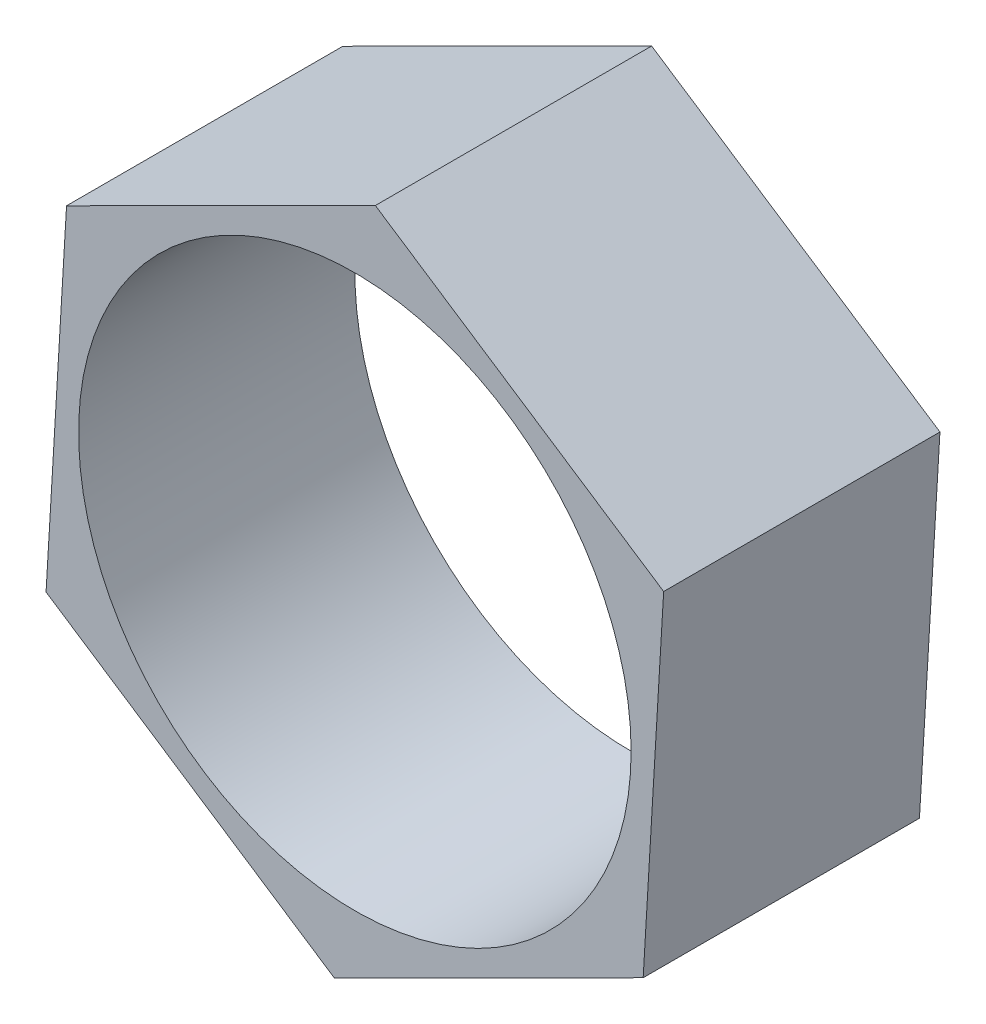
SolidWorks part; units mm, degrees
ref_plane "Front Plane" through (0, 0, 0) normal (0, 0, 1) x (1, 0, 0)
ref_plane "Top Plane" through (0, 0, 0) normal (0, 1, 0) x (1, 0, 0)
ref_plane "Right Plane" through (0, 0, 0) normal (1, 0, 0) x (0, 0, -1)
sketch "Sketch1" plane through (0, 0, 0) normal (0, 0, 1) x (1, 0, 0)
  line L1 (0.0742, 1.2478) -> (-1.0435, 0.6881)
  line L2 (-1.0435, 0.6881) -> (-1.1177, -0.5597)
  line L3 (-1.1177, -0.5597) -> (-0.0742, -1.2478)
  line L4 (-0.0742, -1.2478) -> (1.0435, -0.6881)
  line L5 (1.0435, -0.6881) -> (1.1177, 0.5597)
  line L6 (1.1177, 0.5597) -> (0.0742, 1.2478)
  circle A0 centre (0, 0) radius 1
  circle A1 centre (0, 0) radius 1.0825 construction
  point P3 (-1.299, 0.8258)
  dimension "D1" = 2
  dimension "D2" = 2.5
extrude "Boss-Extrude1" add sketch "Sketch1" along normal blind 1
